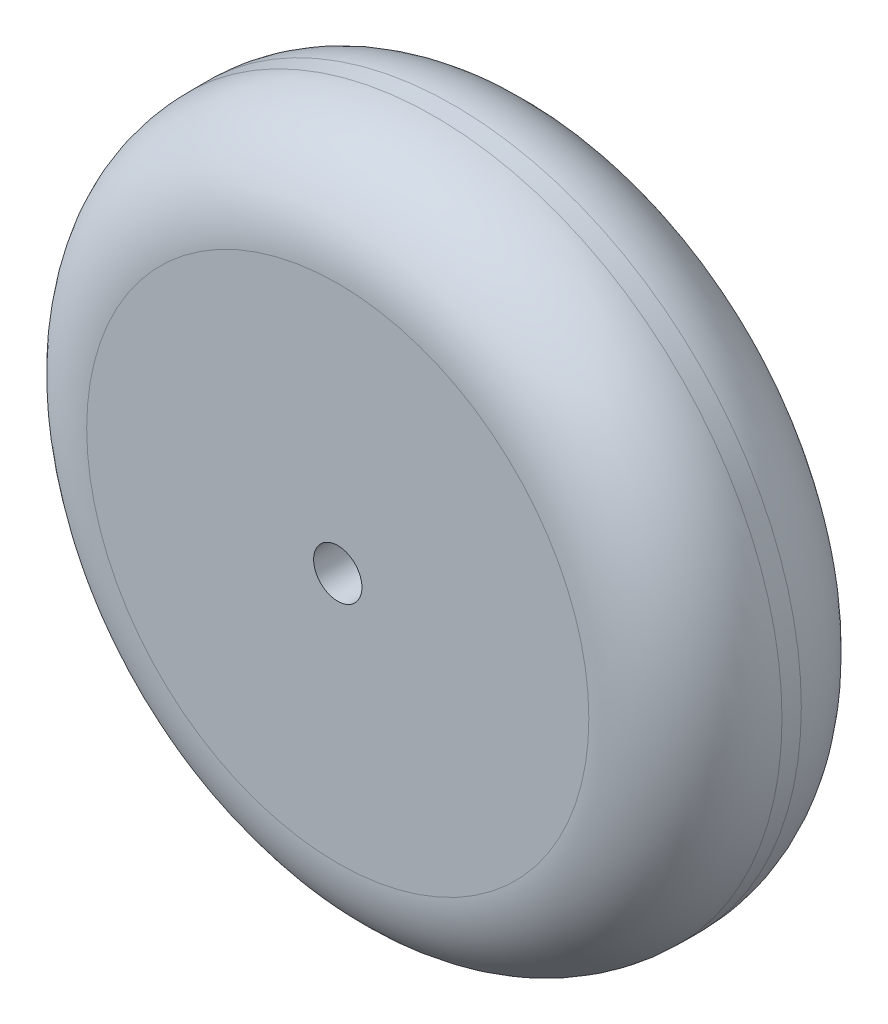
SolidWorks part; units mm, degrees
ref_plane "Front Plane" through (0, 0, 0) normal (0, 0, 1) x (1, 0, 0)
ref_plane "Top Plane" through (0, 0, 0) normal (0, 1, 0) x (1, 0, 0)
ref_plane "Right Plane" through (0, 0, 0) normal (1, 0, 0) x (0, 0, -1)
sketch "Sketch1" plane through (0, 0, 0) normal (0, 0, 1) x (1, 0, 0)
  circle A0 centre (0, 0) radius 36
  dimension "D1" = 72
extrude "Wheel-Base" add sketch "Sketch1" along normal blind 22
sketch "Sketch2" plane through (0, 0, 22) normal (0, 0, 1) x (1, 0, 0)
  circle A0 centre (0, 0) radius 2.5
  dimension "D1" = 5
extrude "Shaft-Hole" cut sketch "Sketch2" against normal through all
fillet "Rounding" radius 10 2 edges at (36, 0, 0) (36, 0, 22)
equation "\"Foamcore\" = .1in"
equation "\"MDF\" = .2in"
equation "\"Gmaterial\"= \"MDF\""
